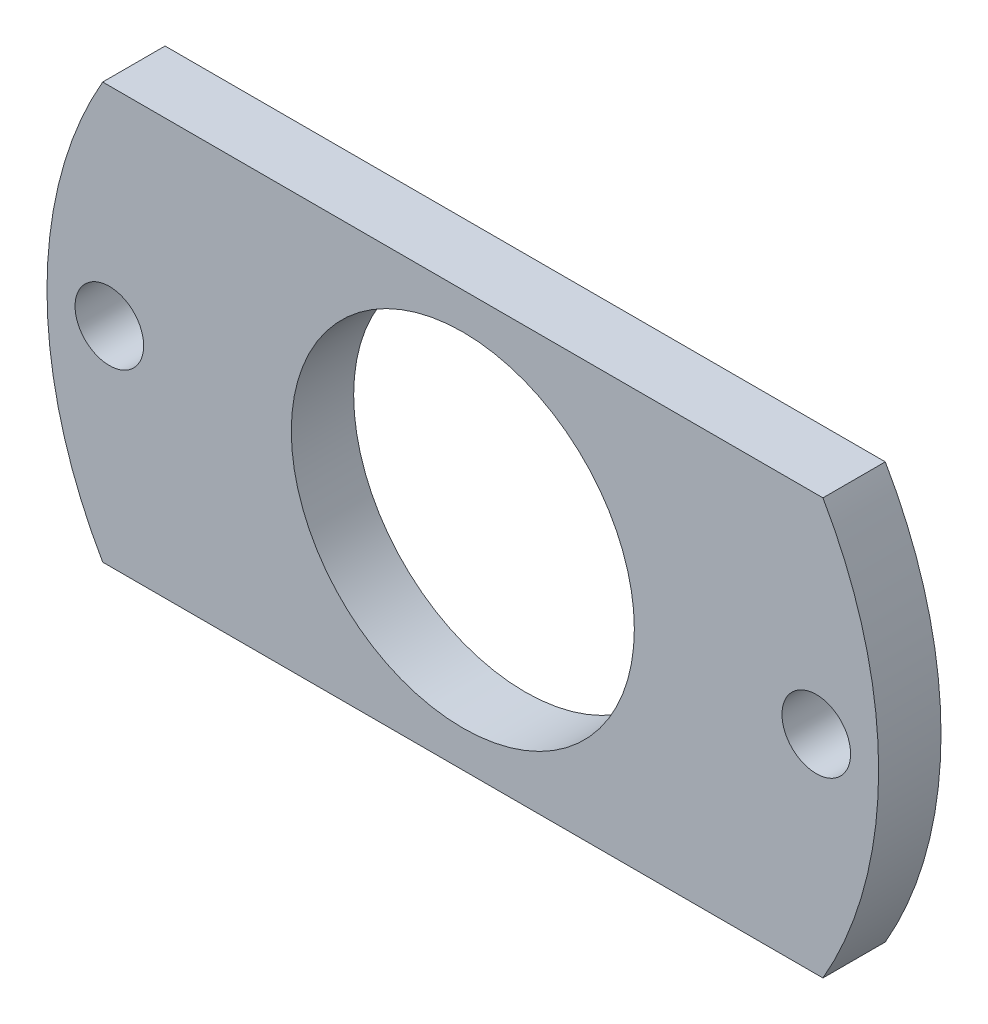
SolidWorks part; units mm, degrees
material "Thornel Mat VMA"
ref_plane "前视基准面" through (0, 0, 0) normal (0, 0, 1) x (1, 0, 0)
ref_plane "上视基准面" through (0, 0, 0) normal (0, 1, 0) x (1, 0, 0)
ref_plane "右视基准面" through (0, 0, 0) normal (1, 0, 0) x (0, 0, -1)
sketch "草图1" plane through (0, 0, 0) normal (0, 0, 1) x (1, 0, 0)
  line L0 (-17.3205, -10) -> (17.3205, -10)
  line L1 (-17.3205, 10) -> (17.3205, 10)
  circle A0 centre (0, 0) radius 8.25
  circle A1 centre (0, 0) radius 20
  circle A2 centre (0, 0) radius 17 construction
  circle A3 centre (0, 17) radius 1.65
  circle A4 centre (-17, 0) radius 1.65
  circle A5 centre (17, 0) radius 1.65
  dimension "D1" = 16.5
  dimension "D2" = 40
  dimension "D3" = 34
  dimension "D4" = 3.3
  dimension "D5" = 10
extrude "凸台-拉伸1" add sketch "草图1" along normal blind 3 contours L0 A1 A5 A4 A3 A0
